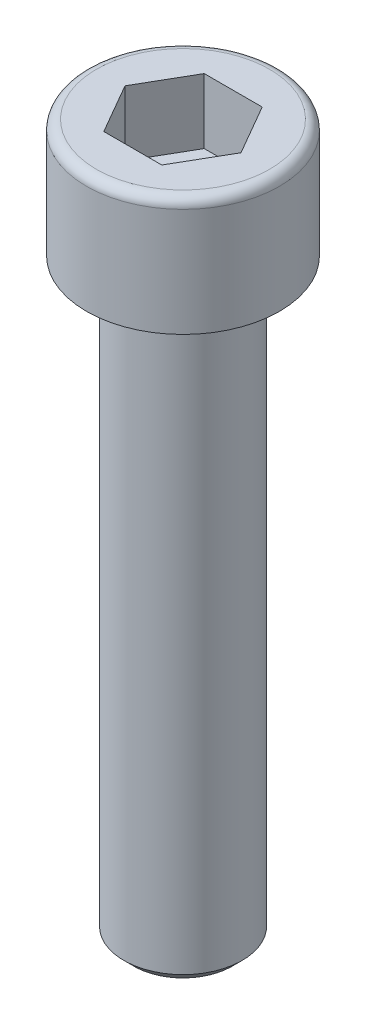
SolidWorks part; units mm, degrees
ref_plane "Plan de face" through (0, 0, 0) normal (0, 0, 1) x (1, 0, 0)
ref_plane "Plan de dessus" through (0, 0, 0) normal (0, 1, 0) x (1, 0, 0)
ref_plane "Plan de droite" through (0, 0, 0) normal (1, 0, 0) x (0, 0, -1)
sketch "Esquisse1" plane through (0, 0, 0) normal (0, 0, 1) x (1, 0, 0)
  line L0 (4.9, 6) -> (0, 6)
  line L1 (0, 6) -> (0, 0)
  line L2 (0, 0) -> (4.9, 0)
  line L3 (4.9, 0) -> (4.9, 6)
  line L4 (0, 6) -> (0, 0) construction
revolve "Révolution1" add sketch "Esquisse1" angle 360 about L4
sketch "Esquisse2" plane through (0, 0, 0) normal (0, -1, 0) x (1, 0, 0)
  circle A0 centre (0, 0) radius 3
extrude "Boss.-Extru.1" add sketch "Esquisse2" along normal blind 30
sketch "Esquisse3" plane through (0, 6, 0) normal (0, 1, 0) x (-1, 0, 0)
  line L0 (1.4722, 2.55) -> (-1.4722, 2.55)
  line L1 (-1.4722, 2.55) -> (-2.9445, 0)
  line L2 (-2.9445, 0) -> (-1.4722, -2.55)
  line L3 (-1.4722, -2.55) -> (1.4722, -2.55)
  line L4 (1.4722, -2.55) -> (2.9445, 0)
  line L5 (2.9445, 0) -> (1.4722, 2.55)
extrude "Enlèv. mat.-Extru.1" cut sketch "Esquisse3" against normal blind 3.3
chamfer "Chanfrein1" distance 0.5 angle 45 1 edges at (0, -30, -3)
fillet "Congé1" radius 0.5 1 edges at (0, 6, -4.9)
